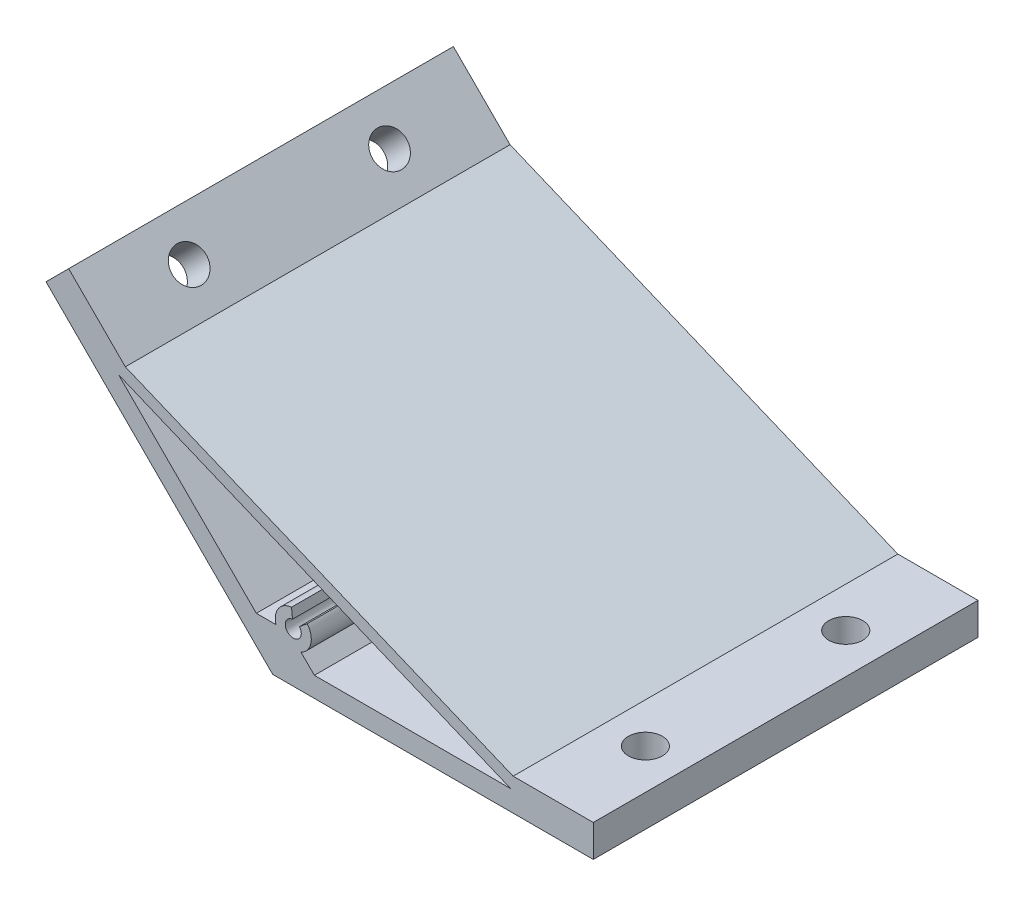
SolidWorks part; units mm, degrees
ref_plane "前视基准面" through (0, 0, 0) normal (0, 0, 1) x (1, 0, 0)
ref_plane "上视基准面" through (0, 0, 0) normal (0, 1, 0) x (1, 0, 0)
ref_plane "右视基准面" through (0, 0, 0) normal (1, 0, 0) x (0, 0, -1)
sketch "草图1" plane through (0, 0, 0) normal (0, 0, 1) x (1, 0, 0)
  line L0 (6992.6877, -1288.6549) -> (7072.6877, -1288.6549)
  line L1 (7003.0909, -1283.6549) -> (7052.0909, -1283.6549)
  line L2 (7052.6877, -1280.6549) -> (7072.6877, -1280.6549)
  line L3 (7003.0909, -1283.6549) -> (7029.4034, -1283.6549)
  line L4 (7072.6877, -1288.6549) -> (7072.6877, -1280.6549)
  line L5 (6997.6265, -1274.2736) -> (6997.3838, -1271.7854)
  line L6 (6999.3656, -1274.9939) -> (7001.2967, -1273.4062)
  line L7 (6992.6877, -1288.6549) -> (6936.1191, -1232.0864)
  line L8 (6988.6024, -1277.4986) -> (6954.2187, -1243.1149)
  line L9 (6955.9181, -1240.5717) -> (6941.776, -1226.4295)
  line L10 (6936.1191, -1232.0864) -> (6941.776, -1226.4295)
  line L11 (6955.9181, -1240.5717) -> (7052.6877, -1280.6549)
  line L12 (6954.2187, -1243.1149) -> (7052.0909, -1283.6549)
  line L13 (7052.0909, -1283.6549) -> (7009.0909, -1283.6549)
  line L14 (7003.0909, -1283.6549) -> (6999.7605, -1280.3246)
  line L15 (6988.6024, -1277.4986) -> (6993.4934, -1277.4986)
  arc A0 (6997.3838, -1271.7854) -> (6993.4934, -1277.4986) centre (6997.8207, -1276.2641) ccw
  arc A1 (6999.7605, -1280.3246) -> (7001.2967, -1273.4062) centre (6997.8207, -1276.2641) ccw
  arc A2 (6997.6265, -1274.2736) -> (6999.3656, -1274.9939) centre (6997.8207, -1276.2641) ccw
extrude "凸台-拉伸1" add sketch "草图1" along normal mid plane 96 contours L11 L9 L10 L7 L0 L4 L2 A2 L5 A0 L15 L8 L12 L1 L3 L14 A1 L6
hole_wizard "Ø8.5 (8.5) 直径孔1" positions "草图3" profile "草图2" hole size "Ø8.5" standard "GB" end condition through all
sketch "草图3" plane through (2852.0164, 2852.0164, 0) normal (-0.7071, -0.7071, 0) x (0.7071, -0.7071, 0)
  line L1 (5775.7935, 48) -> (5775.7935, -48) construction
  line L2 (5795.7935, -48) -> (5775.7935, -48) construction
  point P1 (5785.7935, -25)
  point P18 (5785.7935, 25)
  dimension "D1" = 10
  dimension "D2" = 23
  dimension "D3" = 2
sketch "草图2" plane through (6943.1902, -1239.1575, -25) normal (0, 0, 1) x (0.7071, -0.7071, 0)
  line L0 (0, 0) -> (0, 62.2254)
  line L1 (0, 62.2254) -> (4.25, 62.2254)
  line L2 (4.25, 62.2254) -> (4.25, 0)
  line L5 (4.25, 0) -> (0, 0)
  line L11 (0, -6.35) -> (0, 107.95) construction
  dimension "通孔孔直径" = 8.5
  dimension "通孔孔深度" = 62.2254
sketch "草图4" plane through (580.0623, 1400.3943, 0) normal (0.3827, 0.9239, 0) x (0.9239, -0.3827, 0)
  line L0 (6953.5479, -48) -> (6953.5479, 48) construction
  line L1 (6901.1766, -48) -> (7005.9192, -48) construction
  line L2 (6901.1766, 48) -> (7005.9192, 48) construction
ref_plane "基准面1" through (6424.2406, -2661.0076, 0) normal (-0.9239, 0.3827, 0) x (0, 0, 1)
mirror "镜向1" about plane through (6424.2406, -2661.0076, 0) normal (-0.9239, 0.3827, 0) of "Ø8.5 (8.5) 直径孔1"
